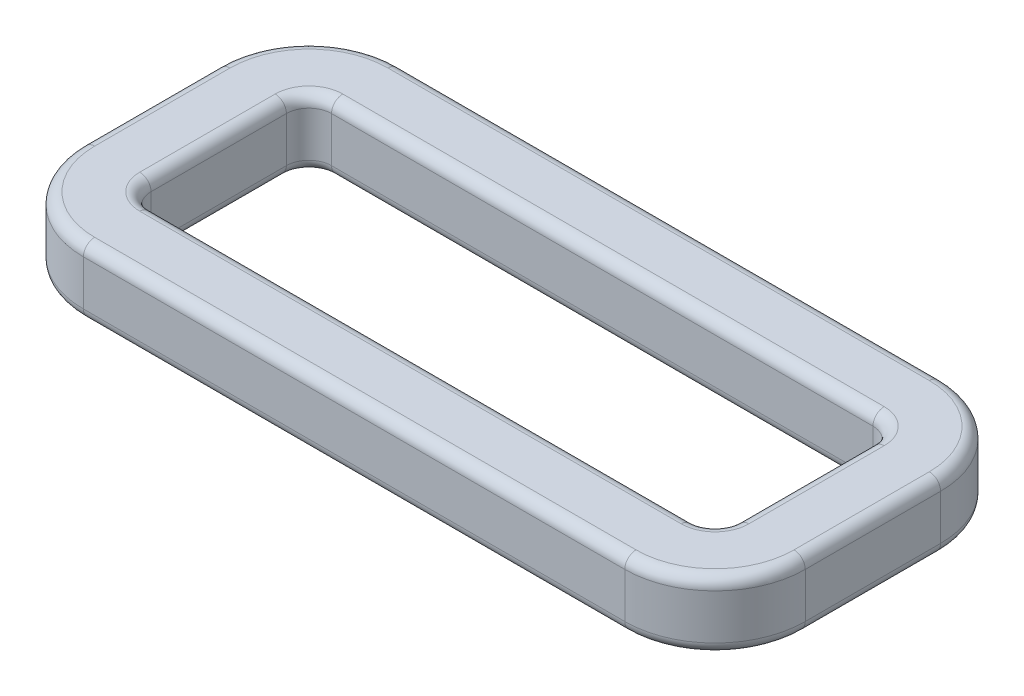
SolidWorks part; units mm, degrees
ref_plane "Front Plane" through (0, 0, 0) normal (0, 0, 1) x (1, 0, 0)
ref_plane "Top Plane" through (0, 0, 0) normal (0, 1, 0) x (1, 0, 0)
ref_plane "Right Plane" through (0, 0, 0) normal (1, 0, 0) x (0, 0, -1)
sketch "Sketch1" plane through (0, 0, 0) normal (0, 1, 0) x (1, 0, 0)
  line L0 (-12, 7) -> (12, 7)
  line L1 (-12, 4) -> (12, 4)
  line L2 (-13, 3) -> (-13, -3)
  line L3 (-12, -4) -> (12, -4)
  line L4 (13, 3) -> (13, -3)
  line L5 (16, 3) -> (16, -3)
  line L6 (-12, -7) -> (12, -7)
  line L7 (-16, 3) -> (-16, -3)
  arc A0 (12, 4) -> (13, 3) centre (12, 3) cw
  arc A1 (12, -4) -> (13, -3) centre (12, -3) ccw
  arc A2 (-13, -3) -> (-12, -4) centre (-12, -3) ccw
  arc A3 (-12, 4) -> (-13, 3) centre (-12, 3) ccw
  arc A4 (12, 7) -> (16, 3) centre (12, 3) cw
  arc A5 (12, -7) -> (16, -3) centre (12, -3) ccw
  arc A6 (-16, -3) -> (-12, -7) centre (-12, -3) ccw
  arc A7 (-12, 7) -> (-16, 3) centre (-12, 3) ccw
  point P4 (0, 4)
  point P6 (13, 0)
  point P9 (13, 4)
  point P12 (13, -4)
  point P17 (-13, 4)
  dimension "D3" = 1
  dimension "D1" = 26
  dimension "D2" = 8
  dimension "D4" = 3
extrude "Boss-Extrude1" add sketch "Sketch1" along normal blind 3 contours L1 A0 L4 A1 L3 A2 L2 A3
fillet "Fillet1" radius 0.5 32 edges at (13, 0, 0) (12.7071, 0, 3.7071) (0, 0, 4) (-12.7071, 0, 3.7071) (-13, 0, 0) (-12.7071, 0, -3.7071) (0, 0, -4) (12.7071, 0, -3.7071) (-16, 0, 0) (-14.8284, 0, 5.8284) (0, 0, 7) (14.8284, 0, 5.8284) (16, 0, 0) (14.8284, 0, -5.8284) (0, 0, -7) (-14.8284, 0, -5.8284) (-12.7071, 3, -3.7071) (-13, 3, 0) (-12.7071, 3, 3.7071) (0, 3, 4) (12.7071, 3, 3.7071) (13, 3, 0) (12.7071, 3, -3.7071) (0, 3, -4) (0, 3, -7) (14.8284, 3, -5.8284) (16, 3, 0) (14.8284, 3, 5.8284) (0, 3, 7) (-14.8284, 3, 5.8284) (-16, 3, 0) (-14.8284, 3, -5.8284)
